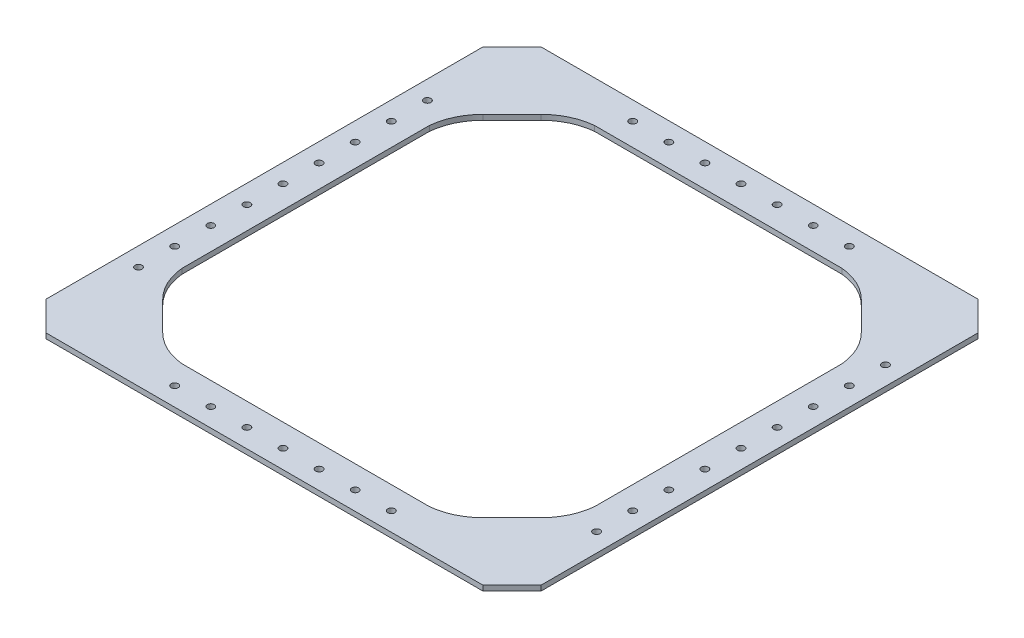
SolidWorks part; units mm, degrees
ref_plane "Front Plane" through (0, 0, 0) normal (0, 0, 1) x (1, 0, 0)
ref_plane "Top Plane" through (0, 0, 0) normal (0, 1, 0) x (1, 0, 0)
ref_plane "Right Plane" through (0, 0, 0) normal (1, 0, 0) x (0, 0, -1)
sketch "Sketch1" plane through (0, 0, 0) normal (0, 1, 0) x (1, 0, 0)
  line L0 (-152.4, 86.2201) -> (-134.4395, 104.1807)
  line L1 (-134.4395, 104.1807) -> (134.4395, 104.1807)
  line L2 (-152.4, 86.2201) -> (-152.4, -182.6588)
  line L3 (152.4, 86.2201) -> (152.4, -182.6588)
  line L4 (152.4, 86.2201) -> (134.4395, 104.1807)
  line L5 (0, 104.1807) -> (0, -200.6193) construction
  line L6 (-152.4, -48.2193) -> (152.4, -48.2193) construction
  line L7 (152.4, -182.6588) -> (134.4395, -200.6193)
  line L8 (-134.4395, -200.6193) -> (134.4395, -200.6193)
  line L9 (-152.4, -182.6588) -> (-134.4395, -200.6193)
  point P9 (0, -48.2193)
  point P11 (0, -48.2193)
  dimension "D1" = 304.8
  dimension "D2" = 304.8
  dimension "D3" = 25.4
  dimension "D4" = 45
extrude "Boss-Extrude1" add sketch "Sketch1" along normal blind 3.175
sketch "Sketch2" plane through (0, 3.175, 0) normal (0, 1, 0) x (1, 0, 0)
  line L0 (-76.2, 78.7807) -> (76.2, 78.7807)
  line L2 (127, -124.4193) -> (127, 27.9807)
  line L3 (98.5185, 68.2596) -> (116.479, 50.2991)
  line L4 (-127, -124.4193) -> (-127, 27.9807)
  line L5 (134.4395, 104.1807) -> (-134.4395, 104.1807) construction
  line L9 (-152.4, 86.2201) -> (-152.4, -182.6588) construction
  line L10 (-134.4395, 104.1807) -> (-152.4, 86.2201) construction
  line L12 (98.5185, -164.6983) -> (116.479, -146.7378)
  line L13 (-76.2, -175.2193) -> (76.2, -175.2193)
  line L14 (-98.5185, -164.6983) -> (-116.479, -146.7378)
  line L15 (152.4, 86.2201) -> (134.4395, 104.1807) construction
  line L20 (-134.4395, 104.1807) -> (-98.5185, 68.2596) construction
  line L21 (-134.4395, 104.1807) -> (-152.4, 86.2201) construction
  line L22 (-152.4, 86.2201) -> (-116.479, 50.2991) construction
  line L23 (-98.5185, 68.2596) -> (-116.479, 50.2991)
  line L24 (0, 104.1807) -> (0, -259.712) construction
  line L25 (-152.4, -48.2193) -> (213.1094, -48.2193) construction
  arc A0 (-98.5185, 68.2596) -> (-76.2, 78.7807) centre (-72.716, 42.4572) cw
  arc A1 (-116.479, 50.2991) -> (-127, 27.9807) centre (-90.6765, 24.4967) ccw
  arc A2 (116.479, 50.2991) -> (127, 27.9807) centre (90.6765, 24.4967) cw
  arc A3 (98.5185, 68.2596) -> (76.2, 78.7807) centre (72.716, 42.4572) ccw
  arc A4 (116.479, -146.7378) -> (127, -124.4193) centre (90.6765, -120.9354) ccw
  arc A5 (98.5185, -164.6983) -> (76.2, -175.2193) centre (72.716, -138.8959) cw
  arc A6 (-98.5185, -164.6983) -> (-76.2, -175.2193) centre (-72.716, -138.8959) ccw
  arc A7 (-116.479, -146.7378) -> (-127, -124.4193) centre (-90.6765, -120.9354) cw
  point P19 (0, 78.7807)
  point P21 (127, -48.2193)
  point P26 (143.4197, 95.2004)
  point P46 (-127, -48.2193)
  dimension "D1" = 25.4
  dimension "D4" = 25.4
  dimension "D5" = 25.4
  dimension "D9" = 50.8
  dimension "D10" = 76.2
  dimension "D11" = 76.2
extrude "Cut-Extrude1" cut sketch "Sketch2" against normal through all
sketch "Sketch4" plane through (0, 3.175, 0) normal (0, 1, 0) x (1, 0, 0)
  line L0 (-152.4, -48.2193) -> (171.6111, -48.2193) construction
  line L1 (-152.4, 86.2201) -> (-152.4, -182.6588) construction
  line L2 (134.4395, 104.1807) -> (-134.4395, 104.1807) construction
  line L3 (0, -48.2193) -> (0, -217.7016) construction
  line L4 (152.4, -182.6588) -> (152.4, 86.2201) construction
  line L5 (0, -48.2193) -> (0, 293.0757) construction
  circle A0 centre (0, 92.7507) radius 2.159
  circle A1 centre (-44.45, 92.7507) radius 2.159
  circle A2 centre (44.45, 92.7507) radius 2.159
  circle A3 centre (-22.225, 92.7507) radius 2.159
  circle A4 centre (22.225, 92.7507) radius 2.159
  circle A5 centre (-140.97, -48.2193) radius 2.159
  circle A6 centre (-140.97, -25.9943) radius 2.159
  circle A7 centre (-140.97, -3.7693) radius 2.159
  circle A8 centre (140.97, -48.2193) radius 2.159
  circle A9 centre (140.97, -25.9943) radius 2.159
  circle A10 centre (140.97, -3.7693) radius 2.159
  circle A11 centre (140.97, -92.6693) radius 2.159
  circle A12 centre (140.97, -70.4443) radius 2.159
  circle A13 centre (-140.97, -92.6693) radius 2.159
  circle A14 centre (-140.97, -70.4443) radius 2.159
  circle A15 centre (22.225, -189.1893) radius 2.159
  circle A16 centre (-22.225, -189.1893) radius 2.159
  circle A17 centre (44.45, -189.1893) radius 2.159
  circle A18 centre (-44.45, -189.1893) radius 2.159
  circle A19 centre (0, -189.1893) radius 2.159
  circle A20 centre (-66.675, 92.7507) radius 2.159
  circle A21 centre (66.675, 92.7507) radius 2.159
  circle A22 centre (-140.97, 18.4557) radius 2.159
  circle A23 centre (140.97, 18.4557) radius 2.159
  circle A24 centre (140.97, -114.8943) radius 2.159
  circle A25 centre (66.675, -189.1893) radius 2.159
  circle A26 centre (-66.675, -189.1893) radius 2.159
  circle A27 centre (-140.97, -114.8943) radius 2.159
  circle A28 centre (-140.97, -137.1193) radius 2.159
  circle A29 centre (-140.97, 40.6807) radius 2.159
  circle A30 centre (140.97, 40.6807) radius 2.159
  circle A31 centre (140.97, -137.1193) radius 2.159
  point P48 (0, 104.1807)
  point P77 (-140.97, -136.4948)
  dimension "D1" = 4.318
  dimension "D2" = 4.318
  dimension "D3" = 4.318
  dimension "D4" = 4.318
  dimension "D5" = 4.318
  dimension "D6" = 4.318
  dimension "D7" = 4.318
  dimension "D8" = 4.318
  dimension "D9" = 4.318
  dimension "D10" = 4.318
  dimension "D11" = 4.318
  dimension "D23" = 4.318
  dimension "D24" = 4.318
  dimension "D27" = 4.318
  dimension "D28" = 4.318
  dimension "D31" = 4.318
  dimension "D12" = 22.225
  dimension "D13" = 22.225
  dimension "D14" = 22.225
  dimension "D15" = 22.225
  dimension "D16" = 22.225
  dimension "D17" = 22.225
  dimension "D18" = 22.225
  dimension "D19" = 22.225
  dimension "D20" = 11.43
  dimension "D21" = 11.43
  dimension "D22" = 11.43
  dimension "D25" = 22.225
  dimension "D26" = 22.225
  dimension "D29" = 22.225
  dimension "D30" = 22.225
  dimension "D32" = 22.225
extrude "Cut-Extrude2" cut sketch "Sketch4" against normal through all
